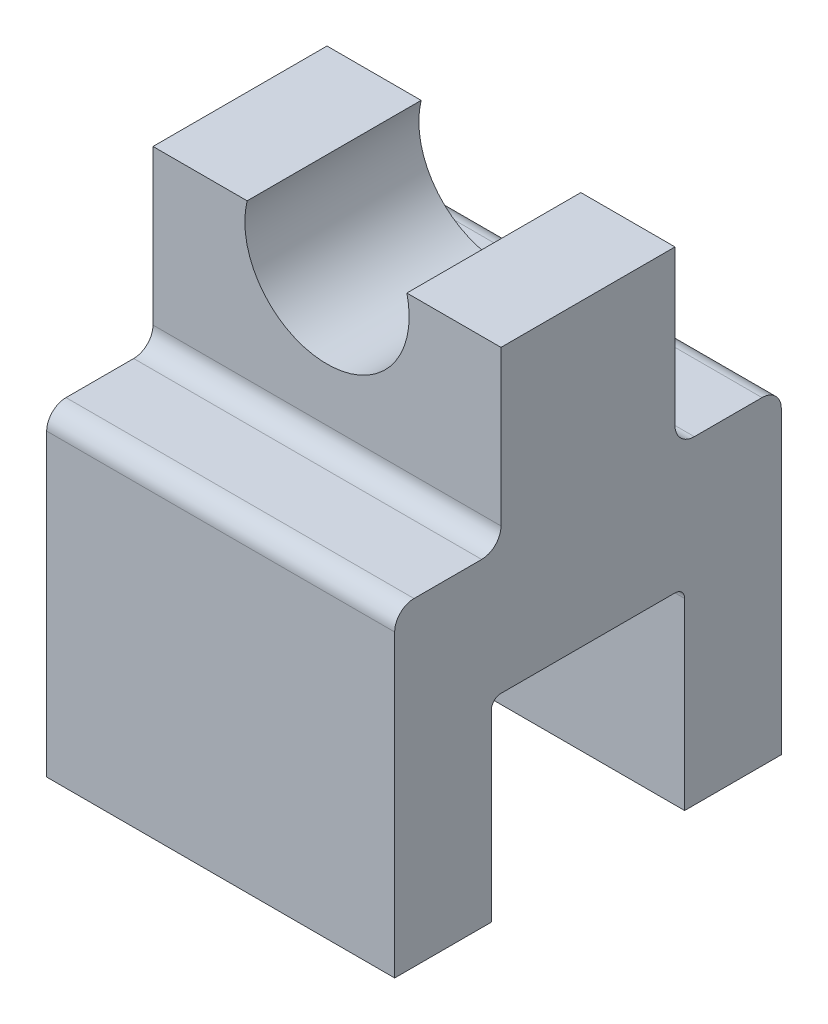
SolidWorks part; units mm, degrees
ref_plane "Front Plane" through (0, 0, 0) normal (0, 0, 1) x (1, 0, 0)
ref_plane "Top Plane" through (0, 0, 0) normal (0, 1, 0) x (1, 0, 0)
ref_plane "Right Plane" through (0, 0, 0) normal (1, 0, 0) x (0, 0, -1)
sketch "Sketch1" plane through (0, 0, 0) normal (0, 0, 1) x (1, 0, 0)
  line L0 (33.3519, 64.77) -> (45.72, 64.77)
  line L1 (0, 0) -> (45.72, 0)
  line L2 (0, 0) -> (0, 64.77)
  line L3 (0, 64.77) -> (12.3681, 64.77)
  line L4 (45.72, 0) -> (45.72, 64.77)
  arc A0 (12.3681, 64.77) -> (33.3519, 64.77) centre (22.86, 62.23) ccw
  dimension "D3" = 21.59
  dimension "D1" = 45.72
  dimension "D2" = 22.86
  dimension "D4" = 62.23
  dimension "D5" = 64.77
extrude "Boss-Extrude1" add sketch "Sketch1" along normal blind 50.8
sketch "Sketch2" plane through (45.72, 0, 0) normal (1, 0, 0) x (0, 0, -1)
  line L0 (-50.8, 0) -> (0, 0) construction
  line L1 (-38.1, 0) -> (-12.7, 0)
  line L2 (-38.1, 0) -> (-38.1, 25.4)
  line L3 (-38.1, 25.4) -> (-12.7, 25.4)
  line L4 (-12.7, 0) -> (-12.7, 25.4)
  line L5 (-50.8, 0) -> (-50.8, 64.77) construction
  dimension "D1" = 25.4
  dimension "D2" = 25.4
  dimension "D3" = 12.7
extrude "Cut-Extrude1" cut sketch "Sketch2" against normal through all
fillet "Fillet1" radius 1.27 2 edges at (22.86, 25.4, 38.1) (22.86, 25.4, 12.7)
sketch "Sketch4" plane through (0, 0, 0) normal (-1, 0, 0) x (0, 0, 1)
  line L1 (50.8, 64.77) -> (36.83, 64.77)
  line L2 (50.8, 64.77) -> (50.8, 41.91)
  line L3 (50.8, 41.91) -> (36.83, 41.91)
  line L4 (36.83, 64.77) -> (36.83, 41.91)
  line L5 (0, 64.77) -> (13.97, 64.77)
  line L6 (0, 64.77) -> (0, 41.91)
  line L7 (0, 41.91) -> (13.97, 41.91)
  line L8 (13.97, 64.77) -> (13.97, 41.91)
  dimension "D1" = 22.86
  dimension "D2" = 22.86
extrude "Cut-Extrude2" cut sketch "Sketch4" against normal through all
fillet "Fillet2" radius 2.54 4 edges at (22.86, 41.91, 0) (22.86, 41.91, 50.8) (22.86, 41.91, 36.83) (22.86, 41.91, 13.97)
